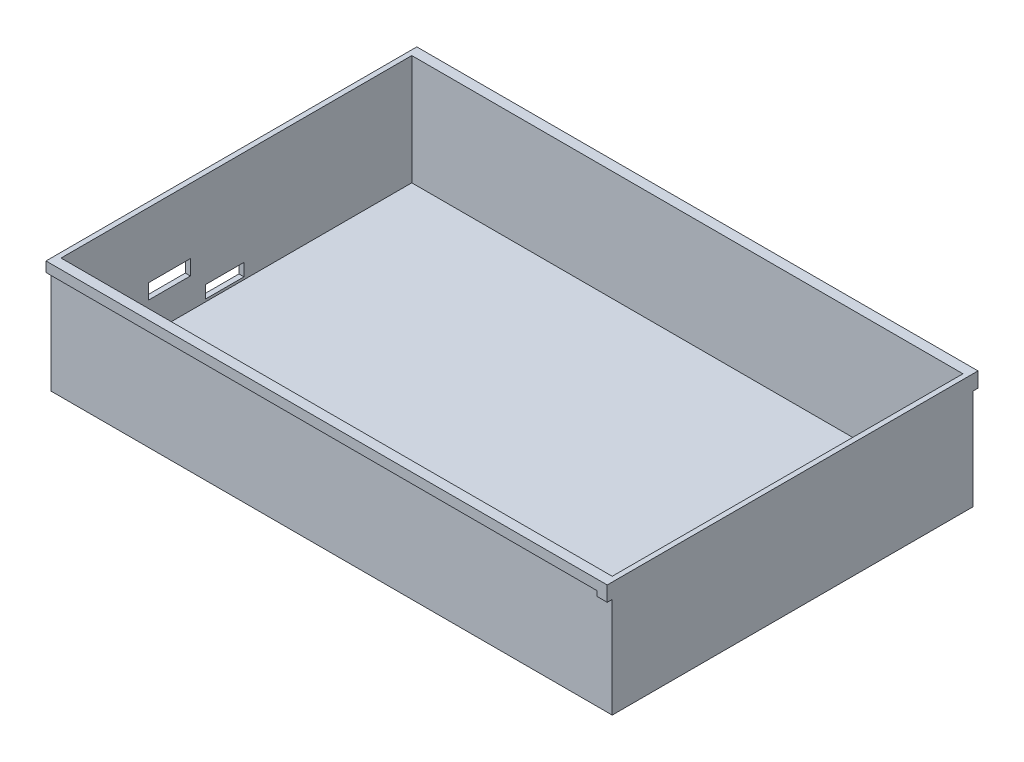
SolidWorks part; units mm, degrees
ref_plane "Alzado" through (0, 0, 0) normal (0, 0, 1) x (1, 0, 0)
ref_plane "Planta" through (0, 0, 0) normal (0, 1, 0) x (1, 0, 0)
ref_plane "Vista lateral" through (0, 0, 0) normal (1, 0, 0) x (0, 0, -1)
sketch "Croquis1" plane through (0, 0, 0) normal (0, 1, 0) x (1, 0, 0)
  line L0 (0, 0) -> (112, 0)
  line L1 (112, 0) -> (112, 72)
  line L2 (112, 72) -> (0, 72)
  line L3 (0, 72) -> (0, 0)
  dimension "D1" = 72
  dimension "D2" = 112
extrude "Saliente-Extruir1" add sketch "Croquis1" along normal blind 1 contours L2 L3 L0 L1
sketch "Croquis2" plane through (0, 0, 0) normal (-1, 0, 0) x (0, 0, 1)
  line L0 (0, 0) -> (0, 23)
  line L1 (0, 23) -> (-72.0074, 23)
  line L2 (-72.0074, 23) -> (-72, 0)
  line L3 (-72, 0) -> (0, 0)
  dimension "D1" = 23
extrude "Saliente-Extruir2" add sketch "Croquis2" against normal blind 1 contours L2 L3 L0 L1
sketch "Croquis3" plane through (112, 0, 0) normal (1, 0, 0) x (0, 0, -1)
  line L0 (0, 0) -> (0, 23)
  line L1 (0, 23) -> (72, 23)
  line L2 (72, 23) -> (72, 0)
  line L3 (72, 0) -> (0, 0)
  dimension "D1" = 23
extrude "Saliente-Extruir3" add sketch "Croquis3" against normal blind 1
sketch "Croquis4" plane through (0, 0, 0) normal (0, 0, 1) x (1, 0, 0)
  line L0 (0, 0) -> (0, 23)
  line L1 (0, 23) -> (112, 23)
  line L2 (112, 23) -> (112, 0)
  line L3 (112, 0) -> (0, 0)
extrude "Saliente-Extruir4" add sketch "Croquis4" against normal blind 1 contours L1 L2 L3 L0
sketch "Croquis5" plane through (0, 0, -72) normal (0, 0, -1) x (-1, 0, 0)
  line L0 (-112, 0) -> (0, 0)
  line L1 (0, 0) -> (0, 23)
  line L2 (0, 23) -> (-112, 23)
  line L3 (-112, 23) -> (-112, 0)
extrude "Saliente-Extruir5" add sketch "Croquis5" against normal blind 1 contours L2 L3 L0 L1
sketch "Croquis6" plane through (0, 0, 0) normal (-1, 0, 0) x (0, 0, 1)
  line L0 (0, 0) -> (0, 10) construction
  line L1 (-18.5, 10) -> (-18.5, 7)
  line L2 (0, 10) -> (-4.5, 10) construction
  line L3 (-17.5, 10) -> (-4.5, 10)
  line L4 (-17.5, 10) -> (-54.5, 10) construction
  line L5 (-54.5, 10) -> (-67.5, 10)
  line L12 (-18.5, 7) -> (-26.8, 7)
  line L13 (-26.8, 7) -> (-26.8, 10)
  line L14 (-26.8, 10) -> (-18.5, 10)
  line L15 (-29.8, 10) -> (-29.8, 4) construction
  line L16 (-29.8, 4) -> (-37.5, 4)
  line L17 (-37.5, 4) -> (-37.5, 1.5)
  line L18 (-37.5, 1.5) -> (-29.8, 1.5)
  line L19 (-29.8, 1.5) -> (-29.8, 4)
  point P10 (0, 0)
  point P11 (0, 0)
  point P12 (0, 0)
  point P13 (0, 0)
  dimension "D1" = 3
  dimension "D2" = 2.5
  dimension "D3" = 10
  dimension "D4" = 63
  dimension "D5" = 4.5
  dimension "D6" = 1
  dimension "D7" = 8.3
  dimension "D8" = 3
  dimension "D9" = 7.7
  dimension "D10" = 6
  dimension "D11" = 27.7
extrude "Cortar-Extruir1" cut sketch "Croquis6" against normal blind 1 contours L18 L19 L16 L17 | L14 L13 L12 L1
sketch "Croquis7" plane through (0, 0, -72) normal (0, 0, -1) x (-1, 0, 0)
  line L0 (-112, 23) -> (0, 23)
  line L1 (0, 23) -> (0, 21)
  line L2 (-110, 21) -> (-110, 20)
  line L3 (-110, 20) -> (-112, 20)
  line L4 (-112, 23) -> (-112, 0) construction
  line L5 (-112, 20) -> (-112, 23)
  line L6 (0, 21) -> (-110, 21)
  dimension "D1" = 3
  dimension "D2" = 2
  dimension "D3" = 1
extrude "Saliente-Extruir6" add sketch "Croquis7" along normal blind 1 contours L0 L1 L6 L2 L3 L5
sketch "Croquis8" plane through (0, 0, 0) normal (0, 0, 1) x (1, 0, 0)
  line L0 (112, 23) -> (112, 20)
  line L1 (112, 23) -> (112, 0) construction
  line L2 (112, 20) -> (110, 20)
  line L3 (110, 20) -> (110, 21)
  line L4 (110, 21) -> (0, 21)
  line L5 (0, 23) -> (0, 0) construction
  line L6 (0, 21) -> (0, 23)
  line L7 (0, 23) -> (112, 23)
  dimension "D1" = 3
  dimension "D2" = 2
  dimension "D3" = 1
extrude "Saliente-Extruir7" add sketch "Croquis8" along normal blind 1
